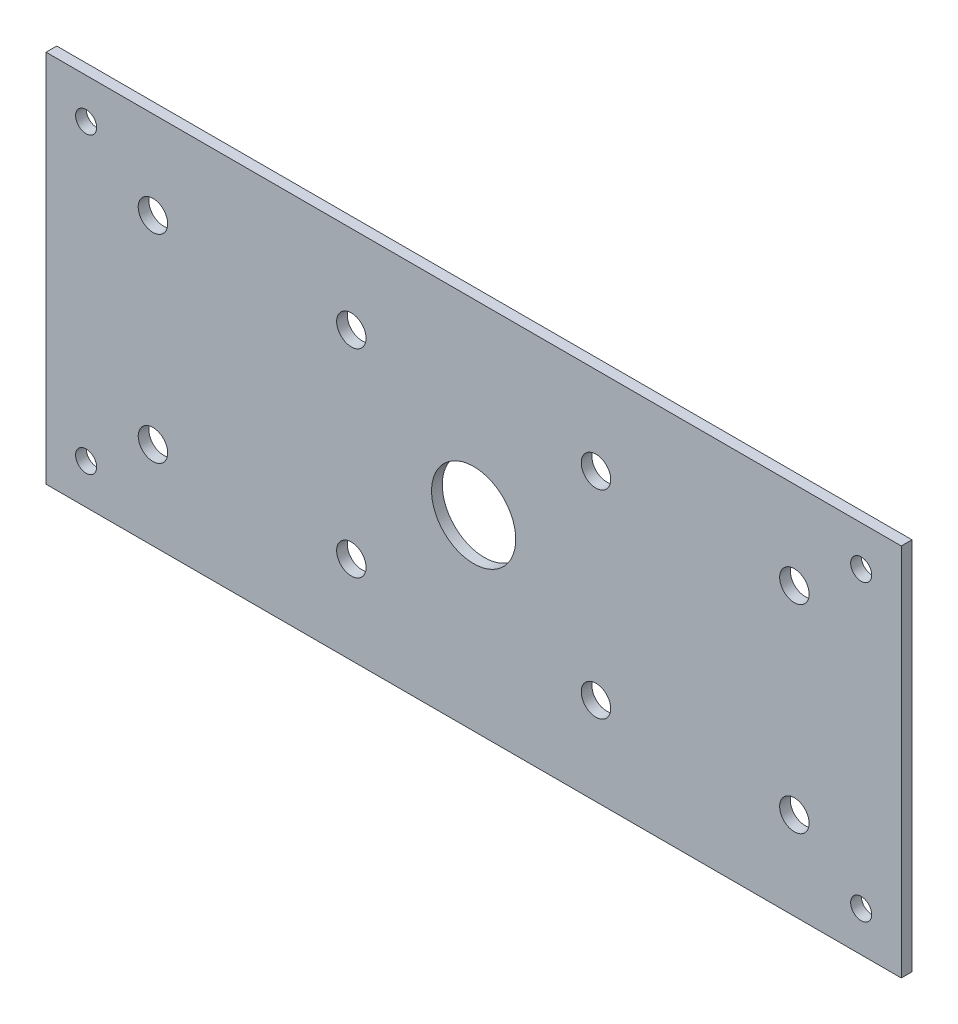
SolidWorks part; units mm, degrees
ref_plane "Front Plane" through (0, 0, 0) normal (0, 0, 1) x (1, 0, 0)
ref_plane "Top Plane" through (0, 0, 0) normal (0, 1, 0) x (1, 0, 0)
ref_plane "Right Plane" through (0, 0, 0) normal (1, 0, 0) x (0, 0, -1)
sketch "Sketch2" plane through (0, 0, 0) normal (0, 0, 1) x (1, 0, 0)
  line L0 (-29.06, 23.57) -> (-76.2, 23.57) construction
  line L1 (-101.6, -44.45) -> (101.6, -44.45)
  line L2 (-101.6, -44.45) -> (-101.6, 44.45)
  line L3 (-101.6, 44.45) -> (101.6, 44.45)
  line L4 (101.6, -44.45) -> (101.6, 44.45)
  line L5 (-101.6, -44.45) -> (101.6, 44.45) construction
  line L6 (-101.6, 44.45) -> (101.6, -44.45) construction
  line L7 (-76.2, 23.57) -> (-76.2, -23.57) construction
  line L8 (-76.2, -23.57) -> (-29.06, -23.57) construction
  line L9 (-29.06, -23.57) -> (-29.06, 23.57) construction
  line L10 (-76.2, 0) -> (-101.6, 0) construction
  line L12 (29.06, -23.57) -> (76.2, -23.57) construction
  line L13 (76.2, -23.57) -> (76.2, 23.57) construction
  line L14 (76.2, 23.57) -> (29.06, 23.57) construction
  line L15 (29.06, 23.57) -> (29.06, -23.57) construction
  line L17 (76.2, 0) -> (101.6, 0) construction
  circle A11 centre (-76.2, 23.57) radius 3.5
  circle A12 centre (-29.06, 23.57) radius 3.5
  circle A13 centre (-29.06, -23.57) radius 3.5
  circle A14 centre (-76.2, -23.57) radius 3.5
  circle A15 centre (29.06, -23.57) radius 3.5
  circle A16 centre (76.2, -23.57) radius 3.5
  circle A17 centre (76.2, 23.57) radius 3.5
  circle A18 centre (29.06, 23.57) radius 3.5
  circle A19 centre (0, 0) radius 10
  point P0 (0, 0)
  point P17 (101.6, 0)
  point P23 (-101.6, 0)
  dimension "D3" = 7
  dimension "D6" = 20
  dimension "D1" = 47.14
  dimension "D2" = 88.9
  dimension "D4" = 203.2
  dimension "D5" = 25.4
extrude "Boss-Extrude1" add sketch "Sketch2" along normal mid plane 2.54
sketch "Sketch3" plane through (0, 0, 1.27) normal (0, 0, 1) x (1, 0, 0)
  line L0 (-101.6, 34.925) -> (-92.075, 34.925) construction
  line L1 (-101.6, 44.45) -> (-101.6, -44.45) construction
  line L2 (-92.075, 34.925) -> (-92.075, 44.45) construction
  line L3 (101.6, 44.45) -> (-101.6, 44.45) construction
  line L4 (92.075, 44.45) -> (92.075, 34.925) construction
  line L5 (92.075, 34.925) -> (101.6, 34.925) construction
  line L6 (101.6, -44.45) -> (101.6, 44.45) construction
  line L7 (92.075, -44.45) -> (92.075, -34.925) construction
  line L8 (-101.6, -44.45) -> (101.6, -44.45) construction
  line L9 (92.075, -34.925) -> (101.6, -34.925) construction
  line L10 (-92.075, -44.45) -> (-92.075, -34.925) construction
  line L11 (-92.075, -34.925) -> (-101.6, -34.925) construction
  circle A0 centre (-92.075, 34.925) radius 2.5
  circle A1 centre (-92.075, -34.925) radius 2.5
  circle A2 centre (92.075, -34.925) radius 2.5
  circle A3 centre (92.075, 34.925) radius 2.5
  dimension "D2" = 5
  dimension "D1" = 9.525
extrude "Cut-Extrude1" cut sketch "Sketch3" against normal through all
